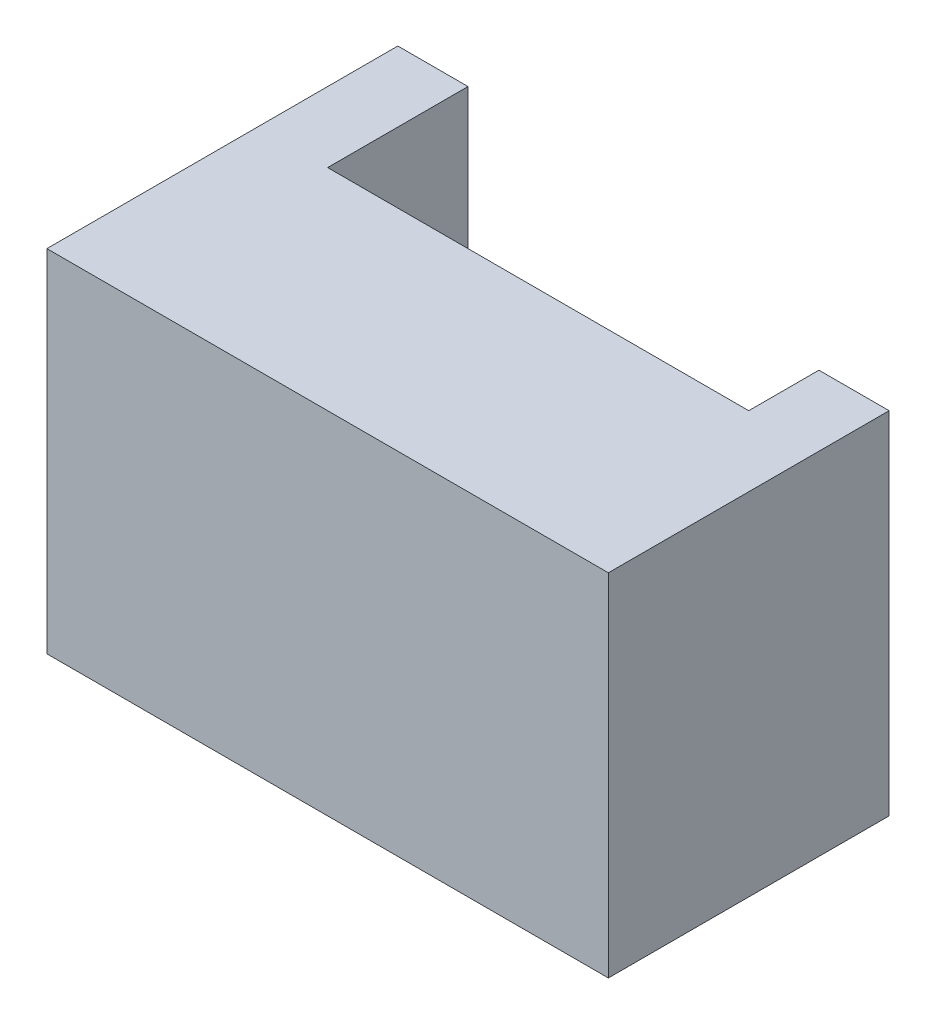
SolidWorks part; units mm, degrees
ref_plane "Front Plane" through (0, 0, 0) normal (0, 0, 1) x (1, 0, 0)
ref_plane "Top Plane" through (0, 0, 0) normal (0, 1, 0) x (1, 0, 0)
ref_plane "Right Plane" through (0, 0, 0) normal (1, 0, 0) x (0, 0, -1)
sketch "Sketch1" plane through (0, 0, 0) normal (0, 1, 0) x (1, 0, 0)
  line L0 (-81.2739, 35.414) -> (-61.2739, 35.414)
  line L2 (-81.2739, 35.414) -> (-81.2739, -64.586)
  line L3 (-81.2739, -64.586) -> (78.7261, -64.586)
  line L4 (78.7261, 15.414) -> (78.7261, -64.586)
  line L7 (-61.2739, 35.414) -> (-61.2739, -4.586)
  line L8 (-61.2739, -4.586) -> (58.7261, -4.586)
  line L9 (58.7261, -4.586) -> (58.7261, 15.414)
  line L10 (58.7261, 15.414) -> (78.7261, 15.414)
  point P0 (0, 0)
  dimension "D1" = 120
  dimension "D2" = 20
  dimension "D3" = 20
  dimension "D4" = 100
  dimension "D5" = 80
  dimension "D6" = 20
extrude "Boss-Extrude1" add sketch "Sketch1" along normal blind 100
